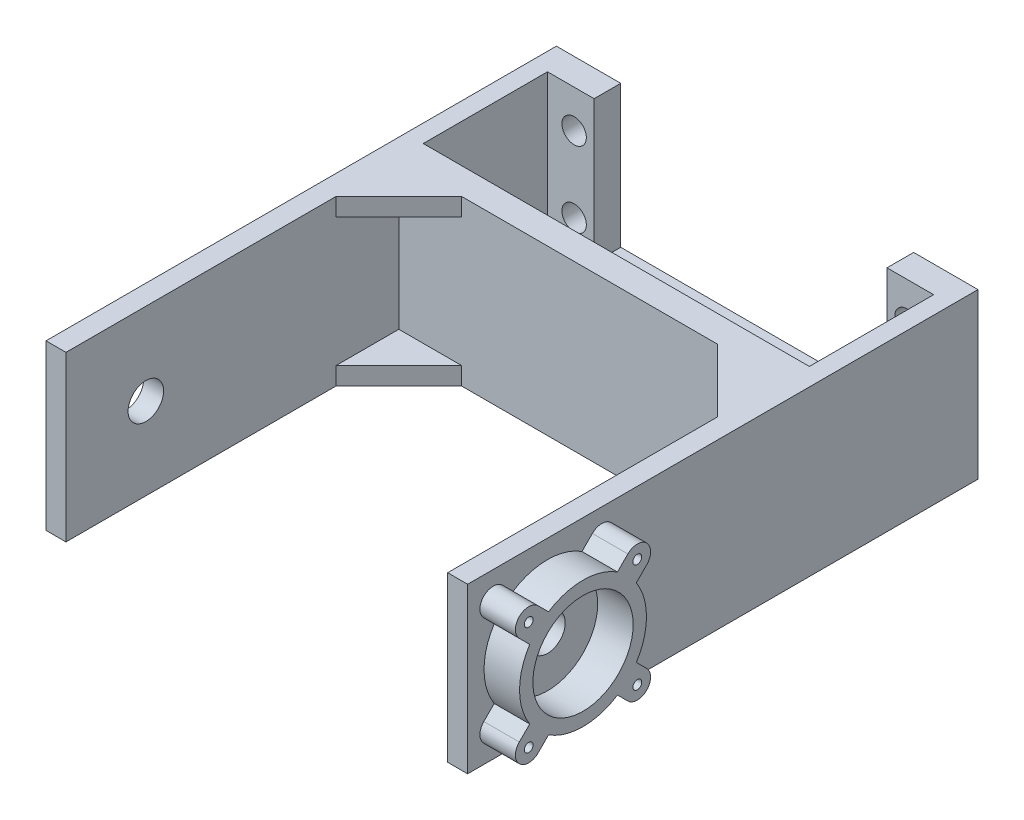
SolidWorks part; units mm, degrees
material "ABS"
ref_plane "Front Plane" through (0, 0, 0) normal (0, 0, 1) x (1, 0, 0)
ref_plane "Top Plane" through (0, 0, 0) normal (0, 1, 0) x (1, 0, 0)
ref_plane "Right Plane" through (0, 0, 0) normal (1, 0, 0) x (0, 0, -1)
sketch "Sketch1" plane through (0, 0, 0) normal (0, 1, 0) x (1, 0, 0)
  line L1 (-47.5, 20) -> (47.5, 20)
  line L2 (-47.5, 20) -> (-47.5, -20)
  line L3 (-47.5, -20) -> (47.5, -20)
  line L4 (47.5, 20) -> (47.5, -20)
  line L5 (-47.5, 20) -> (47.5, -20) construction
  line L6 (-47.5, -20) -> (47.5, 20) construction
  point P0 (0, 0)
  dimension "D1" = 95
  dimension "D2" = 40
extrude "Boss-Extrude1" add sketch "Sketch1" along normal blind 5
sketch "Sketch2" plane through (0, 5, 0) normal (0, 1, 0) x (1, 0, 0)
  line L0 (0, 20) -> (0, -20) construction
  line L1 (-47.5, -20) -> (47.5, -20) construction
  line L2 (-33, 20) -> (-33, -20) construction
  line L3 (47.5, 20) -> (-47.5, 20) construction
  line L4 (-47.5, 20) -> (-47.5, -20) construction
  line L5 (-33, 20) -> (-47.5, 20)
  line L6 (-33, 20) -> (-33, 14)
  line L7 (-33, 14) -> (-47.5, 14)
  line L8 (-47.5, 20) -> (-47.5, 14)
  line L9 (33, 14) -> (47.5, 14)
  line L10 (47.5, 20) -> (47.5, 14)
  line L11 (33, 20) -> (47.5, 20)
  line L12 (33, 20) -> (33, 14)
  point P6 (0, 0)
  dimension "D1" = 33
  dimension "D2" = 6
extrude "Boss-Extrude2" add sketch "Sketch2" along normal blind 32
sketch "Sketch3" plane through (0, 37, 0) normal (0, 1, 0) x (1, 0, 0)
  line L1 (-47.5, 20) -> (47.5, 20)
  line L2 (-47.5, 20) -> (-47.5, 14)
  line L3 (-47.5, 14) -> (47.5, 14)
  line L4 (47.5, 20) -> (47.5, 14)
extrude "Boss-Extrude3" [suppressed] add sketch "Sketch3" against normal blind 6
sketch "Sketch4" plane through (0, 0, -20) normal (0, 0, -1) x (-1, 0, 0)
  line L0 (0, 0) -> (0, 43) construction
  line L2 (-33, 5) -> (33, 5) construction
  circle A0 centre (37.5, 11.5) radius 2.75
  circle A1 centre (37.5, 28.5) radius 2.75
  circle A2 centre (-37.5, 28.5) radius 2.75
  circle A3 centre (-37.5, 11.5) radius 2.75
  dimension "D1" = 5.5
  dimension "D4" = 5.5
  dimension "D2" = 37.5
  dimension "D3" = 17
extrude "Cut-Extrude1" cut sketch "Sketch4" against normal blind 6
sketch "Sketch6" plane through (0, 5, 0) normal (0, 1, 0) x (1, 0, 0)
  line L0 (-47.5, -20) -> (47.5, -20) construction
  line L2 (0, 0) -> (0, -20) construction
  circle A0 centre (-38, 0) radius 2.7
  circle A1 centre (38, 0) radius 2.7
  dimension "D1" = 20
  dimension "D2" = 76
extrude "Cut-Extrude2" [suppressed] cut sketch "Sketch6" against normal blind 6
sketch "Sketch7" plane through (-47.5, 0, 0) normal (-1, 0, 0) x (0, 0, 1)
  line L0 (20, 5) -> (-14, 37)
  line L1 (-14, 37) -> (-14, 5)
  line L2 (-14, 5) -> (20, 5)
extrude "Boss-Extrude4" [suppressed] add sketch "Sketch7" against normal blind 4
mirror "Mirror1" [suppressed] about plane through (0, 0, 0) normal (1, 0, 0)
sketch "Sketch9" [suppressed] plane through (0, 5, 0) normal (0, 1, 0) x (1, 0, 0)
  line L0 (47.5, -20) -> (47.5, 14) construction
  line L1 (-47.5, -20) -> (47.5, -20)
  line L2 (-47.5, -20) -> (-47.5, -14)
  line L3 (-47.5, -14) -> (47.5, -14)
  line L4 (47.5, -20) -> (47.5, -14)
  dimension "D1" = 6
sketch "Sketch10" plane through (0, 5, 0) normal (0, 1, 0) x (1, 0, 0)
  line L0 (47.5, -20) -> (47.5, 14) construction
  line L1 (-47.5, -20) -> (47.5, -20)
  line L2 (-47.5, -20) -> (-47.5, -14)
  line L3 (-43.5, -14) -> (43.5, -14)
  line L4 (47.5, -20) -> (47.5, -19)
  line L5 (-47.5, 14) -> (-33, 14) construction
  line L6 (-47.5, -20) -> (-43.5, -20)
  line L7 (-47.5, -20) -> (-47.5, 14)
  line L8 (-47.5, 14) -> (-43.5, 14)
  line L9 (-43.5, -14) -> (-43.5, 14)
  line L10 (33, 14) -> (47.5, 14) construction
  line L11 (47.5, -20) -> (43.5, -20)
  line L12 (47.5, -20) -> (47.5, 14)
  line L13 (47.5, 14) -> (43.5, 14)
  line L14 (43.5, -14) -> (43.5, 14)
  line M12 (47.5, 14) -> (33, 14)
  line M16 (-33, 14) -> (-47.5, 14)
  line M17 (-47.5, 14) -> (-47.5, -20)
  line M18 (-47.5, -20) -> (47.5, -20)
  line M19 (47.5, -20) -> (47.5, 14)
  dimension "D1" = 6
  dimension "D2" = 4
  dimension "D3" = 4
extrude "Boss-Extrude5" add sketch "Sketch10" along normal blind 32 contours L14 L3 L9 L1 M16 M17 M18 M19 M12
sketch "Sketch11" plane through (0, 0, 20) normal (0, 0, 1) x (1, 0, 0)
  line L0 (0, 0) -> (0, 37) construction
  line L1 (-47.5, 37) -> (47.5, 37) construction
  line L2 (-47.5, 0) -> (47.5, 0) construction
  line L6 (-43, 37) -> (-43, 0)
  line L7 (-43, 0) -> (-47.5, 0)
  line L8 (-47.5, 0) -> (-47.5, 37)
  line L9 (-47.5, 37) -> (-43, 37)
  line L10 (47.5, 0) -> (47.5, 37)
  line L11 (43, 0) -> (47.5, 0)
  line L12 (43, 37) -> (43, 0)
  line L13 (47.5, 37) -> (43, 37)
  dimension "D1" = 43
  dimension "D2" = 4.5
extrude "Boss-Extrude6" add sketch "Sketch11" along normal blind 75
sketch "Sketch12" plane through (-47.5, 0, 0) normal (-1, 0, 0) x (0, 0, 1)
  line L0 (95, 37) -> (95, 0) construction
  circle A0 centre (77, 18.5) radius 4
  dimension "D1" = 18
extrude "Cut-Extrude3" cut sketch "Sketch12" against normal blind 110
sketch "Sketch14" plane through (47.5, 0, 0) normal (1, 0, 0) x (0, 0, -1)
  line L2 (-51.8884, 4.1457) -> (-51.7374, 6.3175)
  line L3 (-47.6457, 8.3884) -> (-50.0959, 10.5765)
  line L6 (-76.3543, 8.3884) -> (-58.0271, -2.1553)
  line L7 (-72.1116, 4.1457) -> (-83.6295, -8.7518)
  line L10 (-72.1116, 32.8543) -> (-56.5863, 37.7326)
  line L11 (-76.3543, 28.6116) -> (-91.7462, 42.3571)
  line L14 (-47.6457, 28.6116) -> (-50.05, 26.266)
  line L15 (-51.8884, 32.8543) -> (-52.5061, 32.1625)
  circle A2 centre (-77, 18.5) radius 25.0466
  arc A3 (-91.7462, 42.3571) -> (-58.0271, -2.1553) centre (-77, 18.5) ccw
  arc A6 (-51.8884, 4.1457) -> (-47.8982, 8.6138) centre (-49.7671, 6.2671) ccw
  circle A7 centre (-49.7671, 6.2671) radius 1
  arc A10 (-76.3543, 8.3884) -> (-71.8862, 4.3982) centre (-74.2329, 6.2671) ccw
  circle A11 centre (-74.2329, 6.2671) radius 1
  arc A14 (-72.1116, 32.8543) -> (-76.1018, 28.3862) centre (-74.2329, 30.7329) ccw
  circle A15 centre (-74.2329, 30.7329) radius 1
  arc A18 (-47.6457, 28.6116) -> (-52.1138, 32.6018) centre (-49.7671, 30.7329) ccw
  circle A19 centre (-49.7671, 30.7329) radius 1
  circle A20 centre (-77, 18.5) radius 28.0466 construction
  arc A21 (-83.6295, -8.7518) -> (-51.7374, 6.3175) centre (-77, 18.5) ccw
  arc A22 (-50.0959, 10.5765) -> (-50.05, 26.266) centre (-77, 18.5) ccw
  arc A23 (-52.5061, 32.1625) -> (-56.5863, 37.7326) centre (-77, 18.5) ccw
  point P64 (-62, 18.5)
  dimension "D1" = 3
extrude "Boss-Extrude8" [suppressed] add sketch "Sketch14" along normal blind 8 contours L15 A23 L10 A14 L11 A3 L6 A10 L7 A21 L2 A6 L3 A22 L14 A18 A2 A7 A11 A15 A19
sketch "Sketch15" plane through (0, 37, 0) normal (0, 1, 0) x (1, 0, 0)
  line L0 (28.8579, -20) -> (43, -34.1421)
  line L1 (-43, -20) -> (43, -20) construction
  line L2 (43, -95) -> (43, -20) construction
  line L3 (0, 0) -> (0, -25.5678) construction
  line L4 (28.8579, -20) -> (43, -20)
  line L5 (43, -20) -> (43, -34.1421)
  line L6 (-28.8579, -20) -> (-43, -20)
  line L7 (-28.8579, -20) -> (-43, -34.1421)
  line L8 (-43, -20) -> (-43, -34.1421)
  dimension "D1" = 20
  dimension "D2" = 45
extrude "Boss-Extrude9" add sketch "Sketch15" against normal blind 4
ref_plane "Plane1" through (0, 18.5, 0) normal (0, 1, 0) x (1, 0, 0)
mirror "Mirror2" about plane through (0, 18.5, 0) normal (0, 1, 0) of "Boss-Extrude9"
sketch "Sketch16" plane through (47.5, 0, 0) normal (1, 0, 0) x (0, 0, -1)
  line L0 (-77, 37) -> (-77, 0) construction
  line L1 (-95, 37) -> (20, 37) construction
  line L2 (-66.8884, 4.1457) -> (-69.2347, 6.4921)
  line L3 (-62.6457, 8.3884) -> (-64.9921, 10.7347)
  line L4 (-95, 0) -> (20, 0) construction
  line L5 (-95, 0) -> (-95, 37) construction
  line L6 (-91.3543, 8.3884) -> (-89.0079, 10.7347)
  line L7 (-87.1116, 4.1457) -> (-84.7653, 6.4921)
  line L8 (-95, 18.5) -> (-53.5634, 18.5) construction
  line L10 (-87.1116, 32.8543) -> (-84.7653, 30.5079)
  line L11 (-91.3543, 28.6116) -> (-89.0079, 26.2653)
  line L14 (-62.6457, 28.6116) -> (-64.9921, 26.2653)
  line L15 (-66.8884, 32.8543) -> (-69.2347, 30.5079)
  circle A0 centre (-77, 18.5) radius 11.3
  arc A1 (-89.0079, 26.2653) -> (-89.0079, 10.7347) centre (-77, 18.5) ccw
  circle A4 centre (-64.7671, 6.2671) radius 1
  arc A5 (-66.8884, 4.1457) -> (-62.6457, 8.3884) centre (-64.7671, 6.2671) ccw
  circle A8 centre (-89.2329, 6.2671) radius 1
  arc A9 (-91.3543, 8.3884) -> (-87.1116, 4.1457) centre (-89.2329, 6.2671) ccw
  circle A12 centre (-89.2329, 30.7329) radius 1
  arc A13 (-87.1116, 32.8543) -> (-91.3543, 28.6116) centre (-89.2329, 30.7329) ccw
  circle A16 centre (-64.7671, 30.7329) radius 1
  arc A17 (-62.6457, 28.6116) -> (-66.8884, 32.8543) centre (-64.7671, 30.7329) ccw
  arc A18 (-69.2347, 30.5079) -> (-84.7653, 30.5079) centre (-77, 18.5) ccw
  arc A19 (-64.9921, 10.7347) -> (-64.9921, 26.2653) centre (-77, 18.5) ccw
  arc A20 (-84.7653, 6.4921) -> (-69.2347, 6.4921) centre (-77, 18.5) ccw
  point P3 (-91.3543, 32.8543)
  point P63 (-77, 18.5)
  dimension "D1" = 22.6
  dimension "D2" = 28.6
  dimension "D3" = 3
  dimension "D4" = 2
  dimension "D5" = 3.3182
  dimension "D6" = 17.3
  dimension "D7" = 20.3
  dimension "D8" = 18
extrude "Boss-Extrude11" add sketch "Sketch16" along normal blind 8
